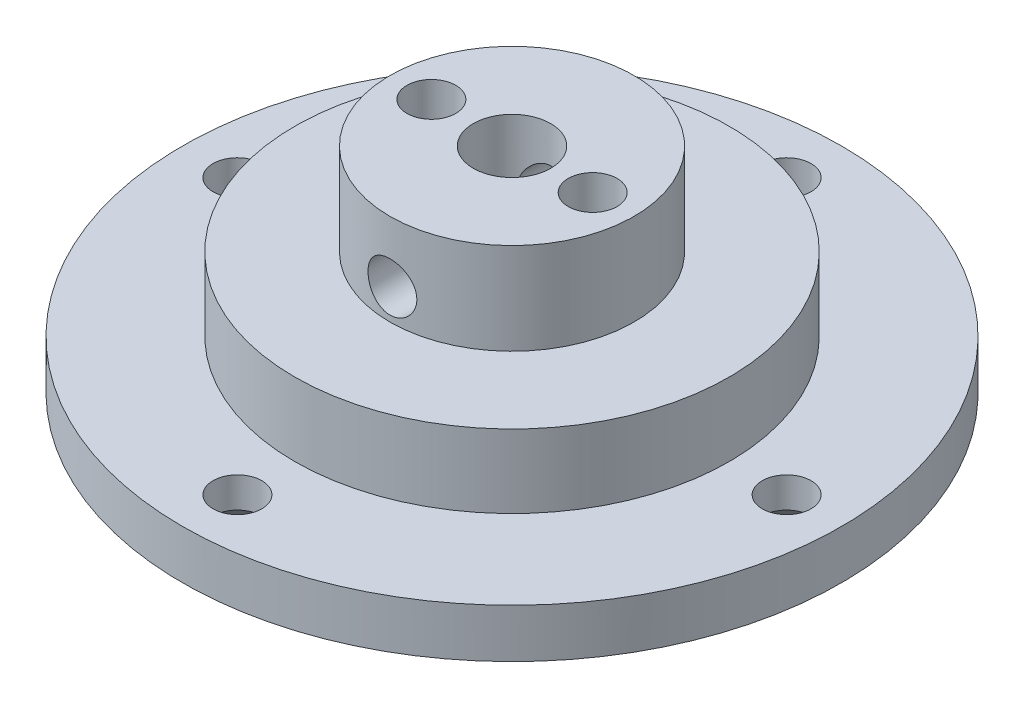
SolidWorks part; units mm, degrees
ref_plane "Спереди" through (0, 0, 0) normal (0, 0, 1) x (1, 0, 0)
ref_plane "Сверху" through (0, 0, 0) normal (0, 1, 0) x (1, 0, 0)
ref_plane "Справа" through (0, 0, 0) normal (1, 0, 0) x (0, 0, -1)
sketch "Эскиз1" plane through (0, 0, 0) normal (0, 1, 0) x (1, 0, 0)
  circle A0 centre (0, 0) radius 27
  circle A1 centre (0, 0) radius 3.175
extrude "Вытянуть1" add sketch "Эскиз1" along normal blind 16
sketch "Эскиз2" plane through (0, 16, 0) normal (0, 1, 0) x (1, 0, 0)
  circle A0 centre (0, 0) radius 10
  circle A1 centre (0, 0) radius 27
extrude "Вырез-Вытянуть1" cut sketch "Эскиз2" against normal blind 7.5
sketch "Эскиз3" plane through (0, 0, 0) normal (0, -1, 0) x (1, 0, 0)
  circle A0 centre (0, 0) radius 15
extrude "Вытянуть2" cut sketch "Эскиз3" against normal blind 6
sketch "Эскиз4" plane through (0, 8.5, 0) normal (0, 1, 0) x (1, 0, 0)
  circle A0 centre (0, 0) radius 27
  circle A1 centre (0, 0) radius 17.8
extrude "Вытянуть3" cut sketch "Эскиз4" against normal blind 6
ref_plane "Плоскость1" through (0, 11, 0) normal (0, 1, 0) x (-1, 0, 0)
sketch "Эскиз5" plane through (0, 0, 0) normal (0, 0, 1) x (1, 0, 0)
  line L0 (11, 11) -> (-11, 11) construction
  circle A0 centre (0, 11) radius 2
extrude "Вытянуть4" cut sketch "Эскиз5" against normal mid plane 32.5
sketch "Эскиз6" plane through (0, 0, 0) normal (0, -1, 0) x (1, 0, 0)
  circle A0 centre (0, 0) radius 15
  circle A1 centre (0, 0) radius 27
extrude "Вытянуть5" add sketch "Эскиз6" along normal blind 1.5
sketch "Эскиз7" plane through (0, 2.5, 0) normal (0, 1, 0) x (1, 0, 0)
  line L0 (0, 27) -> (20.4164, 27) construction
  circle A0 centre (0, 22.5) radius 2
  circle A2 centre (22.5, 0) radius 2
  circle A3 centre (0, -22.5) radius 2
  circle A4 centre (-22.5, 0) radius 2
  dimension "D1" = 4.5
extrude "Вытянуть6" cut sketch "Эскиз7" against normal through all
chamfer "Фаска1" distance 1.5 angle 45 4 edges at (-22.5, -1.5, 2) (0, -1.5, -20.5) (22.5, -1.5, 2) (0, -1.5, 24.5)
sketch "Эскиз8" plane through (0, 16, 0) normal (0, 1, 0) x (1, 0, 0)
  line L0 (-10, 0) -> (12.4288, 0) construction
  line L1 (0, 0) -> (0, 9.1524) construction
  circle A2 centre (-6.6074, 0) radius 2
  circle A3 centre (6.6074, 0) radius 2
extrude "Вытянуть7" cut sketch "Эскиз8" against normal through all
